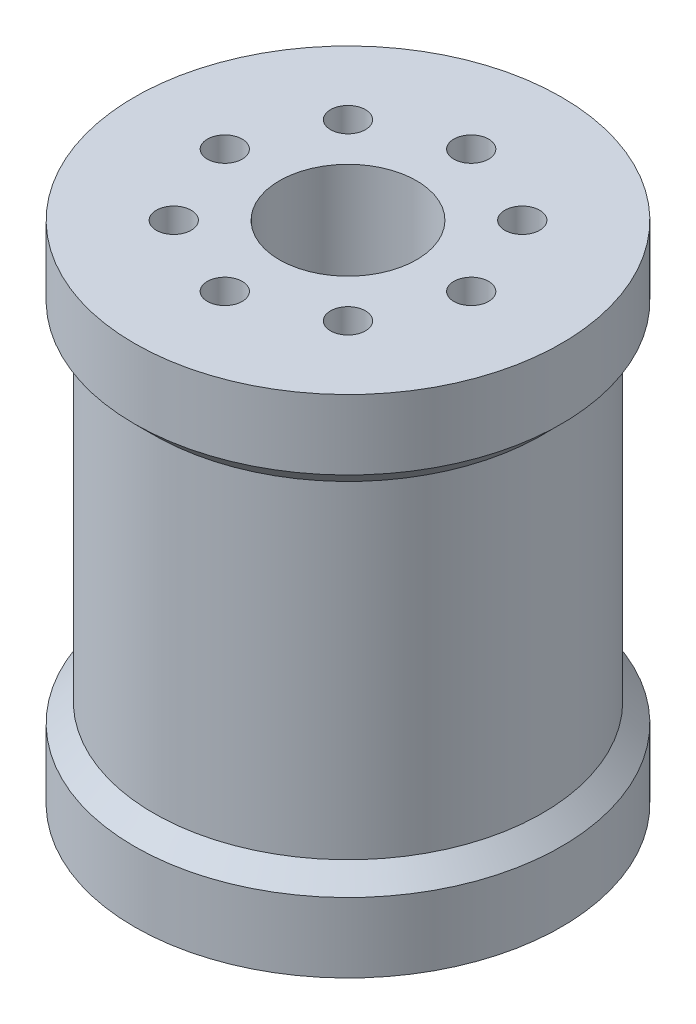
SolidWorks part; units mm, degrees
ref_plane "Front Plane" through (0, 0, 0) normal (0, 0, 1) x (1, 0, 0)
ref_plane "Top Plane" through (0, 0, 0) normal (0, 1, 0) x (1, 0, 0)
ref_plane "Right Plane" through (0, 0, 0) normal (1, 0, 0) x (0, 0, -1)
sketch "Sketch1" plane through (0, 0, 0) normal (0, 0, 1) x (1, 0, 0)
  line L0 (0, 0) -> (0, 29) construction
  line L1 (-3, 0) -> (-3, 29)
  line L2 (-3, 0) -> (-12.25, 0)
  line L3 (-12.25, 0) -> (-12.25, 4)
  line L4 (-12.25, 4) -> (-11.15, 5.1)
  line L5 (-11.15, 5.1) -> (-11.15, 23.9)
  line L6 (-11.15, 23.9) -> (-12.25, 25)
  line L7 (-12.25, 25) -> (-12.25, 29)
  line L8 (-12.25, 29) -> (-3, 29)
  line L9 (-3, 0) -> (0, 0) construction
  line L10 (-3, 29) -> (0, 29) construction
  line L11 (-12.25, 25) -> (-12.25, 4) construction
  point P10 (-7.625, 0)
  dimension "D1" = 12.25
  dimension "D2" = 11.15
  dimension "D3" = 29
  dimension "D4" = 4
  dimension "D5" = 4
  dimension "D6" = 45
  dimension "D7" = 45
  dimension "D8" = 3
revolve "Revolve1" add sketch "Sketch1" angle 360 about L0
sketch "Sketch2" plane through (0, 29, 0) normal (0, 1, 0) x (1, 0, 0)
  line L0 (0, 10.116) -> (0, 0) construction
  line L1 (5, -5) -> (-5, -5) construction
  line L2 (5, -5) -> (5, 5) construction
  line L3 (5, 5) -> (-5, 5) construction
  line L4 (-5, -5) -> (-5, 5) construction
  line L5 (5, -5) -> (-5, 5) construction
  line L6 (5, 5) -> (-5, -5) construction
  line L7 (7.0711, 0) -> (0, 7.0711) construction
  line L8 (7.0711, 0) -> (0, -7.0711) construction
  line L9 (0, 7.0711) -> (-7.0711, 0) construction
  line L10 (0, -7.0711) -> (-7.0711, 0) construction
  line L11 (7.0711, 0) -> (-7.0711, 0) construction
  line L12 (0, 7.0711) -> (0, -7.0711) construction
  circle A0 centre (0, 0) radius 3.935
  circle A1 centre (-5, 5) radius 1
  circle A2 centre (5, 5) radius 1
  circle A3 centre (5, -5) radius 1
  circle A4 centre (-5, -5) radius 1
  circle A5 centre (-7.0711, 0) radius 1
  circle A6 centre (0, 7.0711) radius 1
  circle A7 centre (7.0711, 0) radius 1
  circle A8 centre (0, -7.0711) radius 1
  dimension "D1" = 7.87
  dimension "D3" = 2
  dimension "D2" = 45
  dimension "D4" = 10
  dimension "D5" = 45
  dimension "D6" = 10
extrude "Cut-Extrude1" cut sketch "Sketch2" against normal blind 45
